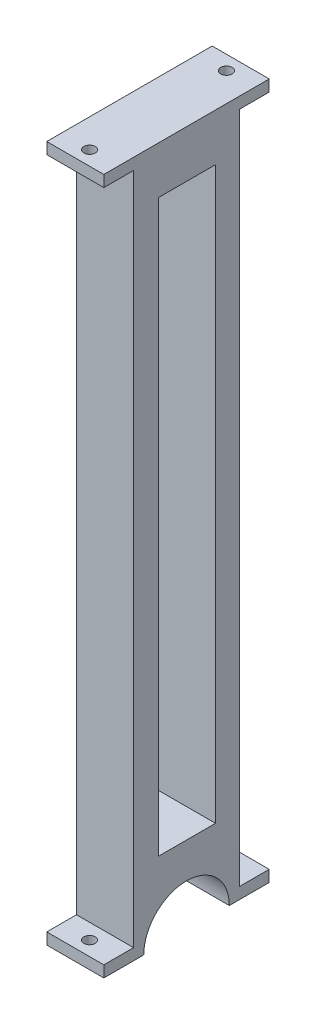
SolidWorks part; units mm, degrees
ref_plane "Front Plane" through (0, 0, 0) normal (0, 0, 1) x (1, 0, 0)
ref_plane "Top Plane" through (0, 0, 0) normal (0, 1, 0) x (1, 0, 0)
ref_plane "Right Plane" through (0, 0, 0) normal (1, 0, 0) x (0, 0, -1)
sketch "Sketch1" plane through (0, 0, 0) normal (1, 0, 0) x (0, 0, -1)
  line L0 (7.5, 0) -> (14.5, 0)
  line L1 (-7.5, 0) -> (-14.5, 0)
  line L2 (-14.5, 0) -> (-14.5, 2)
  line L3 (-14.5, 2) -> (-9.2871, 2)
  line L4 (14.5, 0) -> (14.5, 2)
  line L5 (14.5, 2) -> (9.2871, 2)
  line L6 (9.2871, 2) -> (9.2871, 120)
  line L7 (-9.2871, 2) -> (-9.2871, 120)
  line L8 (-9.2871, 122) -> (9.2871, 122)
  line L9 (-14.5, 122) -> (-9.2871, 122)
  line L10 (9.2871, 122) -> (14.5, 122)
  line L11 (14.5, 122) -> (14.5, 120)
  line L12 (-14.5, 122) -> (-14.5, 120)
  line L13 (-14.5, 120) -> (-9.2871, 120)
  line L14 (14.5, 120) -> (9.2871, 120)
  arc A0 (-7.5, 0) -> (7.5, 0) centre (0, 0) cw
extrude "Boss-Extrude3" add sketch "Sketch1" along normal blind 10 contours L7 L13 L12 L9 L8 L10 L11 L14 L6 L5 L4 L0 A0 L1 L2 L3
sketch "Sketch8" plane through (10, 0, 0) normal (1, 0, 0) x (0, 0, -1)
  line L2 (-4.922, 13.6966) -> (-4.922, 113.6966)
  line L3 (-4.922, 13.6966) -> (5.078, 13.6966)
  line L4 (-4.922, 113.6966) -> (5.078, 113.6966)
  line L5 (5.078, 13.6966) -> (5.078, 113.6966)
  line L6 (-4.922, 13.6966) -> (5.078, 113.6966) construction
  line L7 (-4.922, 113.6966) -> (5.078, 13.6966) construction
  point P4 (0.078, 63.6966)
extrude "Cut-Extrude1" cut sketch "Sketch8" against normal blind 10
sketch "Sketch9" plane through (0, 2, 0) normal (0, 1, 0) x (1, 0, 0)
  circle A0 centre (5, 12) radius 1
extrude "Cut-Extrude2" cut sketch "Sketch9" against normal blind 2
sketch "Sketch11" plane through (0, 2, 0) normal (0, 1, 0) x (1, 0, 0)
  circle A0 centre (5, -12) radius 1
extrude "Cut-Extrude3" cut sketch "Sketch11" against normal blind 2 contours A0
pattern_linear "LPattern1" count 2 spacing 120 along (0, 1, 0) of "Cut-Extrude3", "Cut-Extrude2"
